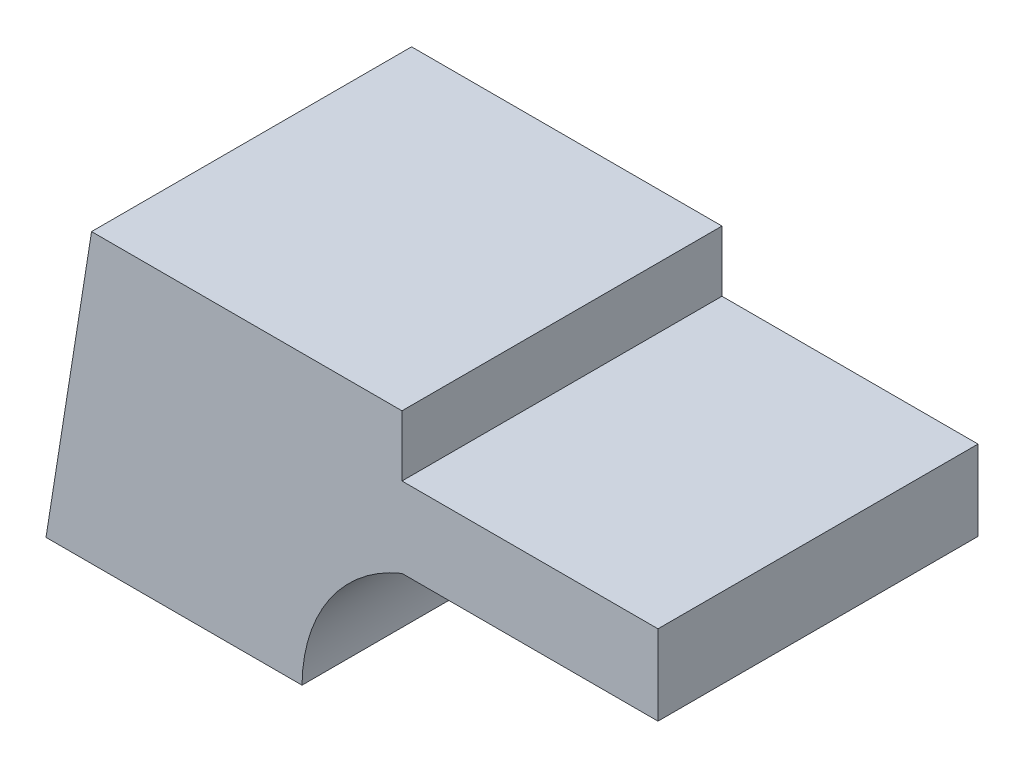
SolidWorks part; units mm, degrees
material "PE High Density"
ref_plane "Front Plane" through (0, 0, 0) normal (0, 0, 1) x (1, 0, 0)
ref_plane "Top Plane" through (0, 0, 0) normal (0, 1, 0) x (1, 0, 0)
ref_plane "Right Plane" through (0, 0, 0) normal (1, 0, 0) x (0, 0, -1)
sketch "Sketch2" plane through (0, 0, 0) normal (0, 0, 1) x (1, 0, 0)
  line L0 (-54.5499, 1.6587) -> (25.4501, 1.6587)
  line L1 (-54.5499, 1.6587) -> (-40.3144, 91.5383)
  line L2 (-40.3144, 91.5383) -> (56.6856, 91.5383)
  line L3 (56.6856, 91.5383) -> (56.6856, 47.5383)
  arc A1 (25.4501, 1.6587) -> (56.6856, 47.5383) centre (75.4479, 1.1921) cw
  dimension "D1" = 97
  dimension "D2" = 91
  dimension "D3" = 80
  dimension "D4" = 81
  dimension "D5" = 44
extrude "Boss-Extrude1" add sketch "Sketch2" along normal blind 100
sketch "Sketch3" plane through (0, 0, 0) normal (0, 0, -1) x (-1, 0, 0)
  line L1 (-56.6856, 47.5383) -> (-136.6856, 47.5383)
  line L2 (-56.6856, 47.5383) -> (-56.6856, 72.5383)
  line L3 (-56.6856, 72.5383) -> (-136.6856, 72.5383)
  line L4 (-136.6856, 47.5383) -> (-136.6856, 72.5383)
  dimension "D1" = 80
  dimension "D2" = 25
extrude "Boss-Extrude2" add sketch "Sketch3" against normal blind 100
